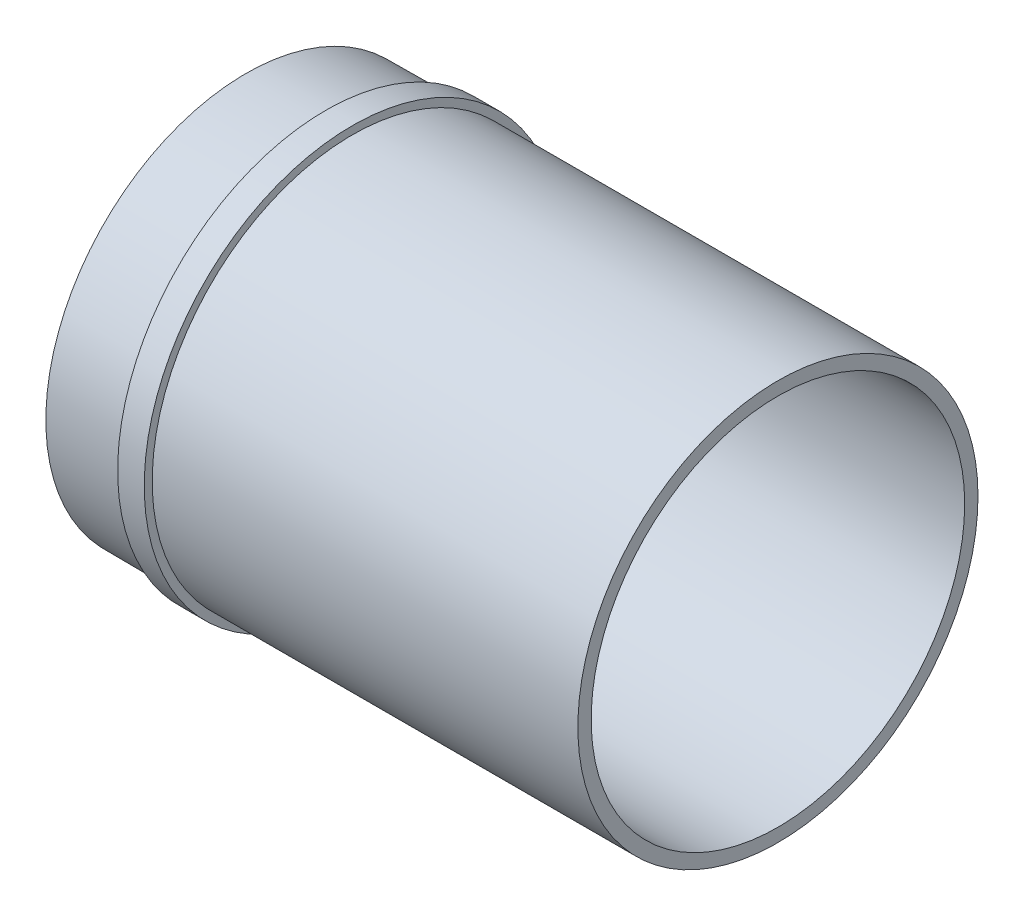
SolidWorks part; units mm, degrees
material "Thornel VCB-20 Carbon Cloth"
ref_plane "Front Plane" through (0, 0, 0) normal (0, 0, 1) x (1, 0, 0)
ref_plane "Top Plane" through (0, 0, 0) normal (0, 1, 0) x (1, 0, 0)
ref_plane "Right Plane" through (0, 0, 0) normal (1, 0, 0) x (0, 0, -1)
sketch "Sketch1" plane through (0, 0, 0) normal (0, 0, 1) x (1, 0, 0)
  line L0 (0, 0) -> (0, 3483.1) construction
  line L1 (0, 3635.5) -> (0, 3632.5)
  line L2 (0, 3557.2968) -> (-750, 3557.2968) construction
  line L3 (0, 3632.5) -> (0, 3635.5) construction
  line L4 (0, 3632.5) -> (160, 3632.5)
  line L5 (-5, 3627.5) -> (160, 3627.5)
  line L6 (-5, 3630.4966) -> (-5, 3627.5)
  line L7 (-750, 3557.2968) -> (-725.3758, 3557.2968)
  line L8 (160, 3632.5) -> (160, 3627.5)
  line L9 (-650, 3576.9205) -> (-650, 3571.8385)
  line L10 (-650, 3571.8385) -> (-600, 3571.8385)
  line L11 (-600, 3571.8385) -> (-600, 3580.5768)
  line L12 (-2.5, 3630) -> (157.5, 3630) construction
  line L13 (-2.5, 3630) -> (157.5, 3630) construction
  line L14 (-725.628, 3559.7968) -> (-725.628, 3559.7968)
  line L15 (-500, 3598.4287) -> (-500, 3595.9046)
  line L18 (157.5, 3630) -> (157.5, 3630)
  line L21 (-2.5, 3632.9991) -> (-2.5, 3630) construction
  line L22 (-2.5, 3632.9991) -> (-2.5, 3630) construction
  line L23 (-470, 3604.991) -> (-470, 3602.4698)
  line L24 (-320, 3621.3893) -> (-320, 3618.8795)
  line L25 (-350, 3616.1014) -> (-350, 3613.5897)
  line L26 (-40, 3632.7798) -> (-40, 3630.2796)
  line L27 (-10, 3632.9862) -> (-10, 3635.4862)
  line L28 (-170, 3629.0204) -> (-170, 3631.5231)
  line L29 (-200, 3627.4907) -> (-200, 3624.9869)
  line L30 (-40, 3630.2796) -> (-40, 3627.5)
  line L31 (-40, 3627.5) -> (-5, 3627.5)
  line L32 (-10, 3632.9862) -> (-10, 3632.6862)
  line L33 (-170, 3629.0204) -> (-170, 3628.7201)
  line L34 (-320, 3618.8795) -> (-320, 3618.5784)
  line L35 (-470, 3602.4698) -> (-470, 3602.1673)
  arc A0 (0, 3635.5) -> (-750, 3557.2968) centre (0, 0) ccw
  arc A1 (-5, 3630.4966) -> (-600, 3580.5768) centre (0, 0) ccw
  arc A2 (-5, 3630.4966) -> (-748.9685, 3552.4043) centre (0, 0) ccw construction
  arc A5 (-650, 3571.8385) -> (-725.3758, 3557.2968) centre (0, 0) ccw
  arc A6 (-5, 3630.4966) -> (-725.3758, 3557.2968) centre (0, 0) ccw construction
  arc A7 (-2.5, 3632.9991) -> (-725.628, 3559.7968) centre (0, 0) ccw construction
  arc A8 (-2.5, 3632.9991) -> (-725.628, 3559.7968) centre (0, 0) ccw construction
  arc A9 (-500, 3598.4287) -> (-470, 3602.4698) centre (0, 0) cw
  arc A10 (-350, 3616.1014) -> (-320, 3618.8795) centre (0, 0) cw
  arc A11 (-10, 3632.9862) -> (-40, 3632.7798) centre (0, 0) ccw
  arc A12 (-170, 3629.0204) -> (-200, 3627.4907) centre (0, 0) ccw
  arc A13 (-40, 3632.4798) -> (-10, 3632.6862) centre (0, 0) cw
  arc A14 (-200, 3627.1903) -> (-170, 3628.7201) centre (0, 0) cw
  arc A15 (-350, 3615.8) -> (-320, 3618.5784) centre (0, 0) cw
  arc A16 (-500, 3598.1258) -> (-470, 3602.1673) centre (0, 0) cw
  dimension "D1" = 7271
  dimension "D7" = 100
  dimension "D10" = 30
  dimension "D8" = 3633
  dimension "D12" = 3633
  dimension "D15" = 3633
  dimension "D18" = 3633
  dimension "D21" = 3632.7
  dimension "D23" = 3632.7
  dimension "D22" = 3632.7
  dimension "D24" = 3632.7
  dimension "D2" = 152.4
  dimension "D3" = 750
  dimension "D4" = 3
  dimension "D5" = 160
  dimension "D9" = 50
  dimension "D11" = 180
  dimension "D13" = 30
  dimension "D14" = 180
  dimension "D16" = 30
  dimension "D17" = 200
  dimension "D19" = 30
  dimension "D20" = 180
  dimension "D6" = 5
revolve "Revolve1" add sketch "Sketch1" angle 360 about L2
